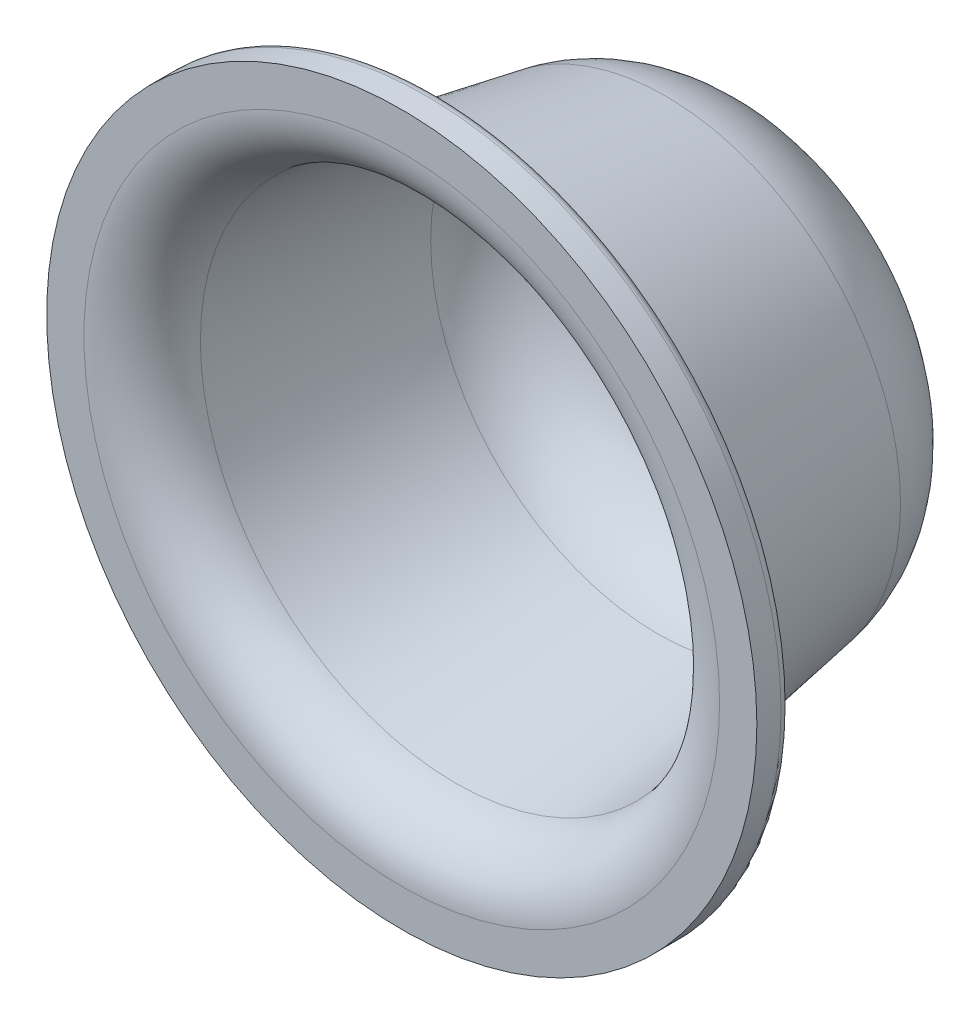
SolidWorks part; units mm, degrees
material "Nitrile Rubber"
ref_plane "Front Plane" through (0, 0, 0) normal (0, 0, 1) x (1, 0, 0)
ref_plane "Top Plane" through (0, 0, 0) normal (0, 1, 0) x (1, 0, 0)
ref_plane "Right Plane" through (0, 0, 0) normal (1, 0, 0) x (0, 0, -1)
sketch "Sketch1" plane through (0, 0, 0) normal (1, 0, 0) x (0, 0, -1)
  line L0 (0, 0) -> (108.735, 0) construction
  line L1 (0, 50) -> (3.4, 50)
  line L2 (0, 50) -> (0, 44.75)
  line L3 (7.6274, 35.9848) -> (36.084, 32.0158)
  line L4 (7.1581, 38.3912) -> (37.1257, 33.1071)
  line L5 (52, 15.3805) -> (52, 0)
  line L6 (3.4, 47.2) -> (3.2, 47.2)
  line L7 (2.2, 46.2) -> (2.2, 44.3)
  line L8 (48.15, 18.15) -> (48.15, 0)
  line L9 (48.15, 0) -> (52, 0)
  line L10 (7.1581, 38.3912) -> (6.8378, 36.095) construction
  line L11 (37.1257, 33.1071) -> (36.9565, 31.8941) construction
  arc A0 (3.4, 50) -> (3.4, 47.2) centre (3.4, 48.6) cw
  arc A1 (2.2, 44.3) -> (7.1581, 38.3912) centre (8.2, 44.3) ccw
  arc A2 (52, 15.3805) -> (37.1257, 33.1071) centre (34, 15.3805) ccw
  arc A3 (0, 44.75) -> (7.6274, 35.9848) centre (8.85, 44.75) ccw
  arc A4 (36.084, 32.0158) -> (48.15, 18.15) centre (34.15, 18.15) cw
  arc A5 (3.2, 47.2) -> (2.2, 46.2) centre (3.2, 46.2) ccw
  dimension "D2" = 4.8
  dimension "D6" = 6
  dimension "D7" = 18
  dimension "D10" = 8.85
  dimension "D13" = 10
  dimension "D14" = 14
  dimension "D15" = 1
  dimension "D9" = 36.3
  dimension "D1" = 100
  dimension "D3" = 2.8
  dimension "D4" = 2.2
  dimension "D5" = 88.6
  dimension "D8" = 52
  dimension "D11" = 89.5
  dimension "D12" = 3.85
  dimension "D16" = 2.3184
  dimension "D17" = 1.2247
revolve "Revolve1" add sketch "Sketch1" angle 360 about L0
